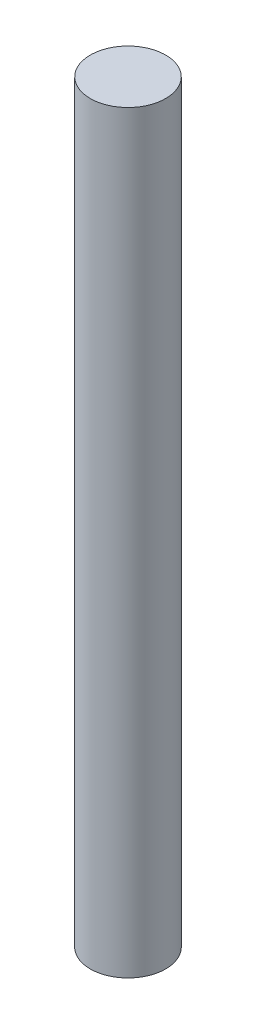
SolidWorks part; units mm, degrees
material "1.5714 (16NiCr4)"
ref_plane "前视基准面" through (0, 0, 0) normal (0, 0, 1) x (1, 0, 0)
ref_plane "上视基准面" through (0, 0, 0) normal (0, 1, 0) x (1, 0, 0)
ref_plane "右视基准面" through (0, 0, 0) normal (1, 0, 0) x (0, 0, -1)
sketch "草图1" plane through (0, 0, 0) normal (0, 1, 0) x (1, 0, 0)
  circle A0 centre (0, 0) radius 7.5
  dimension "D1" = 15
extrude "凸台-拉伸1" add sketch "草图1" along normal blind 150
